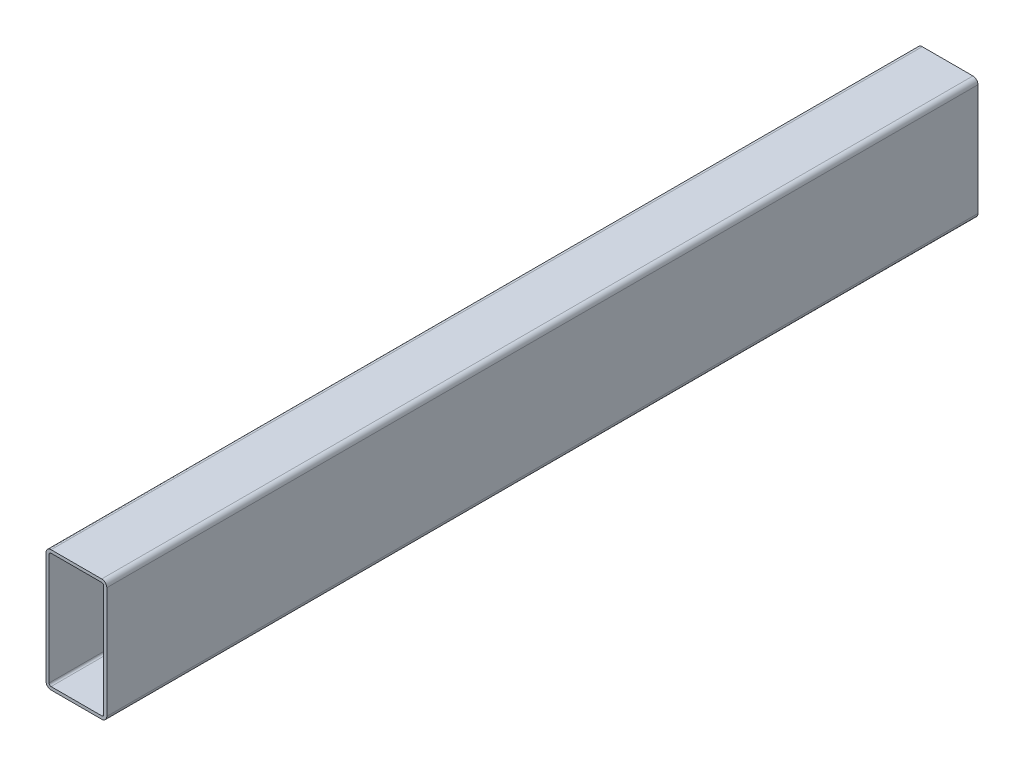
SolidWorks part; units mm, degrees
ref_plane "Front Plane" through (0, 0, 0) normal (0, 0, 1) x (1, 0, 0)
ref_plane "Top Plane" through (0, 0, 0) normal (0, 1, 0) x (1, 0, 0)
ref_plane "Right Plane" through (0, 0, 0) normal (1, 0, 0) x (0, 0, -1)
sketch "Sketch1" plane through (0, 0, 0) normal (0, 0, 1) x (1, 0, 0)
  line L1 (-25, -60) -> (25, -60)
  line L2 (-30, -55) -> (-30, 55)
  line L3 (-25, 60) -> (25, 60)
  line L4 (30, -55) -> (30, 55)
  line L5 (-30, -60) -> (30, 60) construction
  line L6 (-30, 60) -> (30, -60) construction
  arc A0 (30, -55) -> (25, -60) centre (25, -55) cw
  arc A1 (-25, -60) -> (-30, -55) centre (-25, -55) cw
  arc A2 (-30, 55) -> (-25, 60) centre (-25, 55) cw
  arc A3 (25, 60) -> (30, 55) centre (25, 55) cw
  point P0 (0, 0)
  dimension "D3" = 5
  dimension "D1" = 60
  dimension "D2" = 120
extrude "Extrude-Thin1" add sketch "Sketch1" along normal blind 430 and the other way blind 430 thin thin type one direction reverse wall 3
